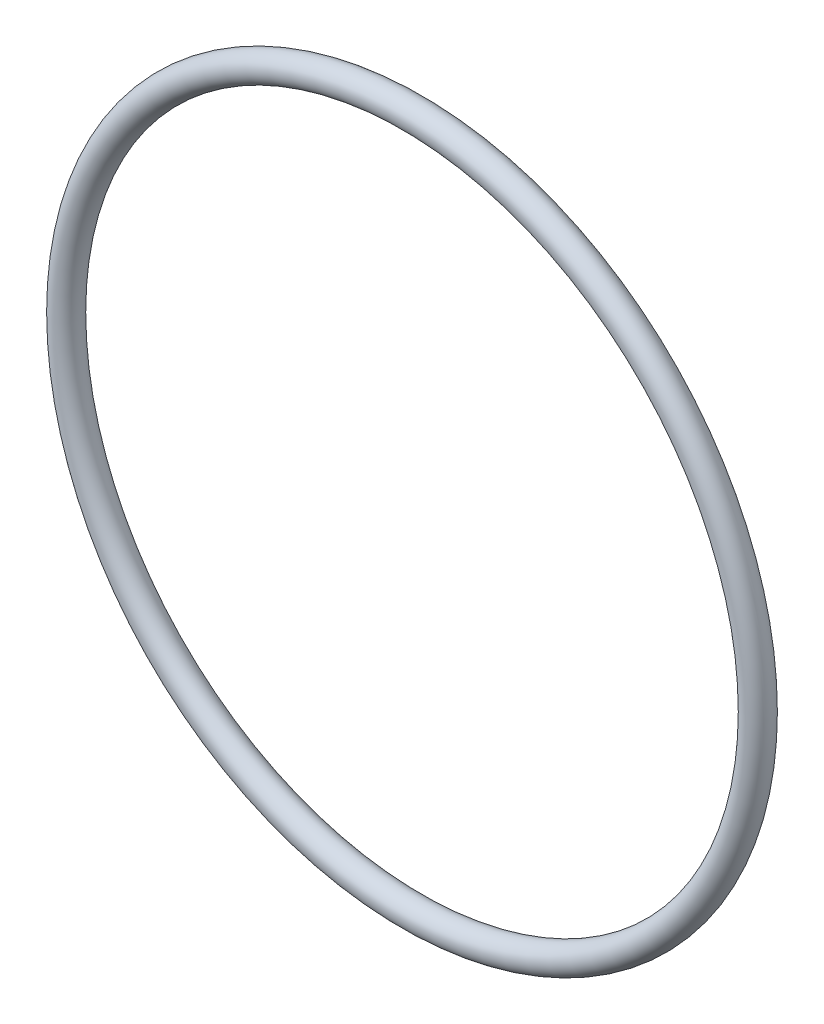
SolidWorks part; units mm, degrees
material "Silicon Rubber"
ref_plane "Front Plane" through (0, 0, 0) normal (0, 0, 1) x (1, 0, 0)
ref_plane "Top Plane" through (0, 0, 0) normal (0, 1, 0) x (1, 0, 0)
ref_plane "Right Plane" through (0, 0, 0) normal (1, 0, 0) x (0, 0, -1)
sketch "Sketch1" plane through (0, 0, 0) normal (0, 0, 1) x (1, 0, 0)
  circle A0 centre (0, 0) radius 38.1
  dimension "D1" = 76.2
sweep "Sweep1" add path "Sketch1" circular profile diameter 3.048 parameters "D3"=3.048
